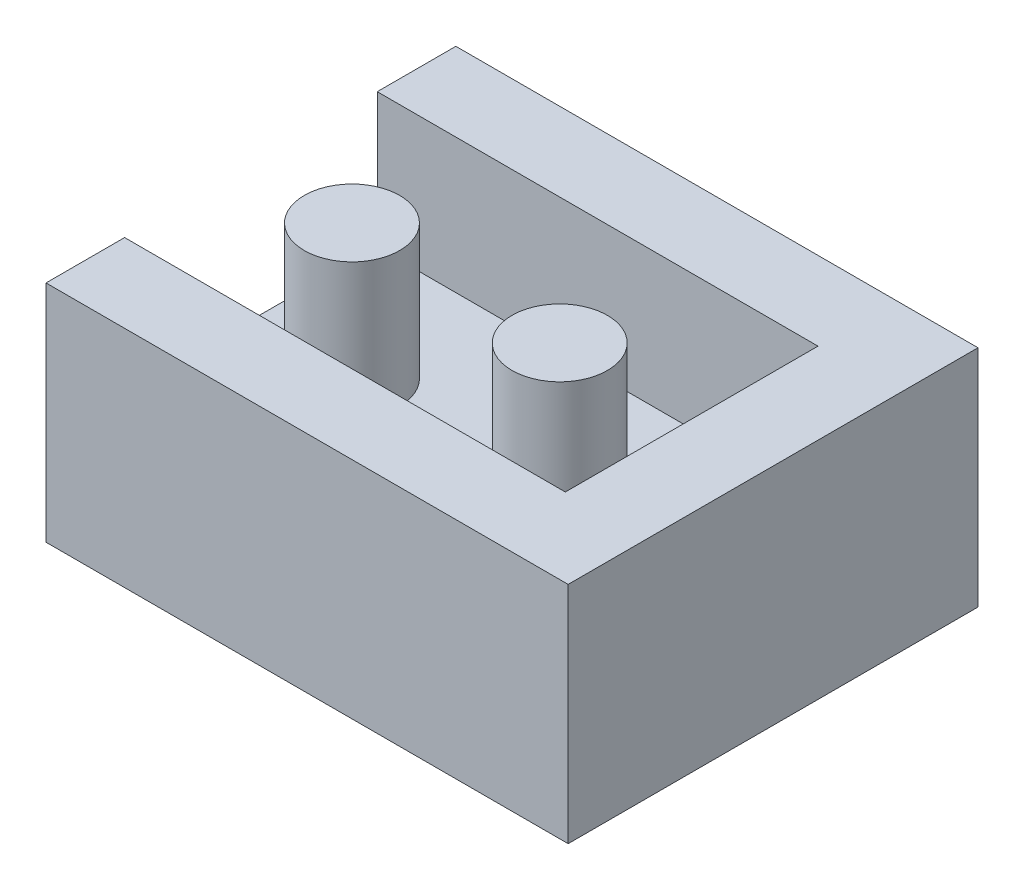
SolidWorks part; units mm, degrees
ref_plane "Front Plane" through (0, 0, 0) normal (0, 0, 1) x (1, 0, 0)
ref_plane "Top Plane" through (0, 0, 0) normal (0, 1, 0) x (1, 0, 0)
ref_plane "Right Plane" through (0, 0, 0) normal (1, 0, 0) x (0, 0, -1)
sketch "Sketch1" plane through (0, 0, 0) normal (0, 1, 0) x (1, 0, 0)
  line L0 (9.3, 0) -> (-9.3, 0) construction
  line L1 (-9.3, -7.3) -> (9.3, -7.3)
  line L2 (-9.3, -7.3) -> (-9.3, 7.3)
  line L3 (-9.3, 7.3) -> (9.3, 7.3)
  line L4 (9.3, -7.3) -> (9.3, 7.3)
  line L5 (-9.3, -7.3) -> (9.3, 7.3) construction
  line L6 (-9.3, 7.3) -> (9.3, -7.3) construction
  line L8 (9.3, 7.3) -> (6.3, 7.3)
  line L9 (9.3, 7.3) -> (9.3, -7.3)
  line L10 (9.3, -7.3) -> (6.3, -7.3)
  line L11 (6.3, 7.3) -> (6.3, -7.3)
  circle A0 centre (-5.8, 0) radius 1.7
  circle A1 centre (1.6, 0) radius 1.7
  point P0 (0, 0)
  point P10 (-4.1, 0)
  point P13 (3.3, 0)
  point P14 (-0.1, 0)
  point P33 (0, 0)
  dimension "D3" = 3.4
  dimension "D1" = 18.6
  dimension "D2" = 14.6
  dimension "D4" = 4
  dimension "D5" = 6
  dimension "D6" = 3
extrude "Boss-Extrude1" add sketch "Sketch1" along normal blind 3.2 contours L11 L3 L2 L1 A1 A0 | L3 L11 L1 L4 | A1 | A0
sketch "Sketch4" plane through (0, 3.2, 0) normal (0, 1, 0) x (1, 0, 0)
  line L0 (9.4, 0) -> (-9.3, 0) construction
  line L1 (-9.3, -7.3) -> (9.4, -7.3)
  line L2 (-9.3, -7.3) -> (-9.3, 7.3)
  line L3 (-9.3, 7.3) -> (9.4, 7.3)
  line L4 (9.4, -7.3) -> (9.4, 7.3)
  line L5 (-9.3, -7.3) -> (9.4, 7.3) construction
  line L6 (-9.3, 7.3) -> (9.4, -7.3) construction
  line L7 (9.4, 7.3) -> (6.4, 7.3)
  line L8 (9.4, 7.3) -> (9.4, -7.3)
  line L9 (9.4, -7.3) -> (6.4, -7.3)
  line L10 (6.4, 7.3) -> (6.4, -7.3)
  line L12 (-9.3, 7.3) -> (6.4, 7.3)
  line L13 (-9.3, 7.3) -> (-9.3, 4.5)
  line L14 (-9.3, 4.5) -> (6.4, 4.5)
  line L15 (6.4, 7.3) -> (6.4, 4.5)
  line L16 (6.4, -7.3) -> (-9.3, -7.3)
  line L17 (6.4, -7.3) -> (6.4, -4.5)
  line L18 (6.4, -4.5) -> (-9.3, -4.5)
  line L19 (-9.3, -7.3) -> (-9.3, -4.5)
  circle A0 centre (-5.7, 0) radius 1.7
  circle A1 centre (1.7, 0) radius 1.7
  point P0 (0.05, 0)
  point P9 (-4, 0)
  point P12 (3.4, 0)
  point P13 (0, 0)
  point P16 (0, 0)
  line M13 (-9.3, -7.3) -> (9.3, -7.3)
  line M14 (9.3, -7.3) -> (9.3, 7.3)
  line M15 (9.3, 7.3) -> (-9.3, 7.3)
  dimension "D3" = 3.4
  dimension "D1" = 18.7
  dimension "D2" = 14.6
  dimension "D4" = 4
  dimension "D5" = 6
  dimension "D6" = 3
  dimension "D7" = 2.8
  dimension "D8" = 2.8
extrude "Boss-Extrude3" add sketch "Sketch4" along normal blind 4.8 contours L2 L14 L10 L3 | L10 L1 M15 M14 | A0 | A1 | L10 L18 L2 M13
sketch "Sketch6" plane through (0, 8, 0) normal (0, 1, 0) x (1, 0, 0)
  line L0 (-9.3, -7.3) -> (9.3, -7.3) construction
  line L1 (-6.9, 4.9) -> (6.9, 4.9) construction
  line L2 (-6.9, 4.9) -> (-6.9, -4.9) construction
  line L3 (-6.9, -4.9) -> (6.9, -4.9) construction
  line L4 (6.9, 4.9) -> (6.9, -4.9) construction
  line L5 (-6.9, 4.9) -> (6.9, -4.9) construction
  line L6 (-6.9, -4.9) -> (6.9, 4.9) construction
  line L8 (9.3, -7.3) -> (9.3, 7.3) construction
  circle A0 centre (6.9, -4.9) radius 1.8
  circle A1 centre (6.9, 4.9) radius 1.8
  point P0 (0, 0)
  dimension "D3" = 3.6
  dimension "D1" = 2.4
  dimension "D2" = 2.4
